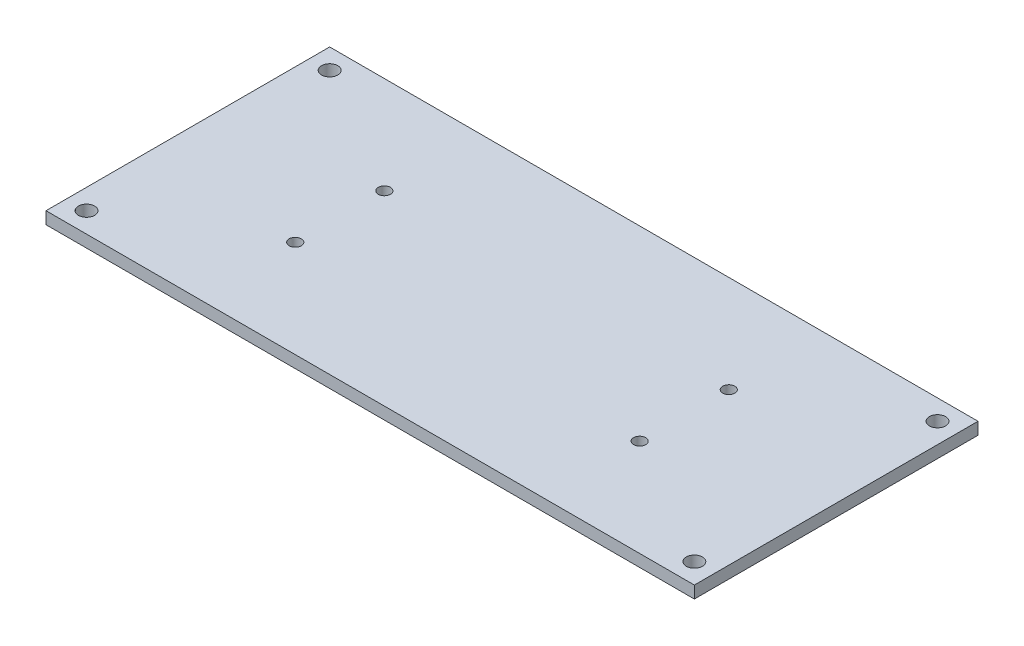
SolidWorks part; units mm, degrees
ref_plane "前视基准面" through (0, 0, 0) normal (0, 0, 1) x (1, 0, 0)
ref_plane "上视基准面" through (0, 0, 0) normal (0, 1, 0) x (1, 0, 0)
ref_plane "右视基准面" through (0, 0, 0) normal (1, 0, 0) x (0, 0, -1)
sketch "Sketch1" plane through (0, 0, 0) normal (0, 1, 0) x (1, 0, 0)
  line L1 (-80, 35) -> (80, 35)
  line L2 (-80, 35) -> (-80, -35)
  line L3 (-80, -35) -> (80, -35)
  line L4 (80, 35) -> (80, -35)
  line L5 (-80, 35) -> (80, -35) construction
  line L6 (-80, -35) -> (80, 35) construction
  point P0 (0, 0)
extrude "Extrude1" add sketch "Sketch1" along normal blind 3
sketch "Sketch2" plane through (0, 3, 0) normal (0, 1, 0) x (1, 0, 0)
  circle A0 centre (-75, 30) radius 2
  circle A1 centre (-75, -30) radius 2
  circle A2 centre (75, -30) radius 2
  circle A3 centre (75, 30) radius 2
extrude "Extrude2" cut sketch "Sketch2" against normal blind 120
sketch "Sketch3" plane through (0, 3, 0) normal (0, 1, 0) x (1, 0, 0)
  circle A0 centre (-42.5, 11) radius 1.5
  circle A1 centre (-42.5, -11) radius 1.5
  circle A2 centre (42.5, -11) radius 1.5
  circle A3 centre (42.5, 11) radius 1.5
  point P0 (0, 0)
extrude "Extrude3" cut sketch "Sketch3" against normal blind 10
